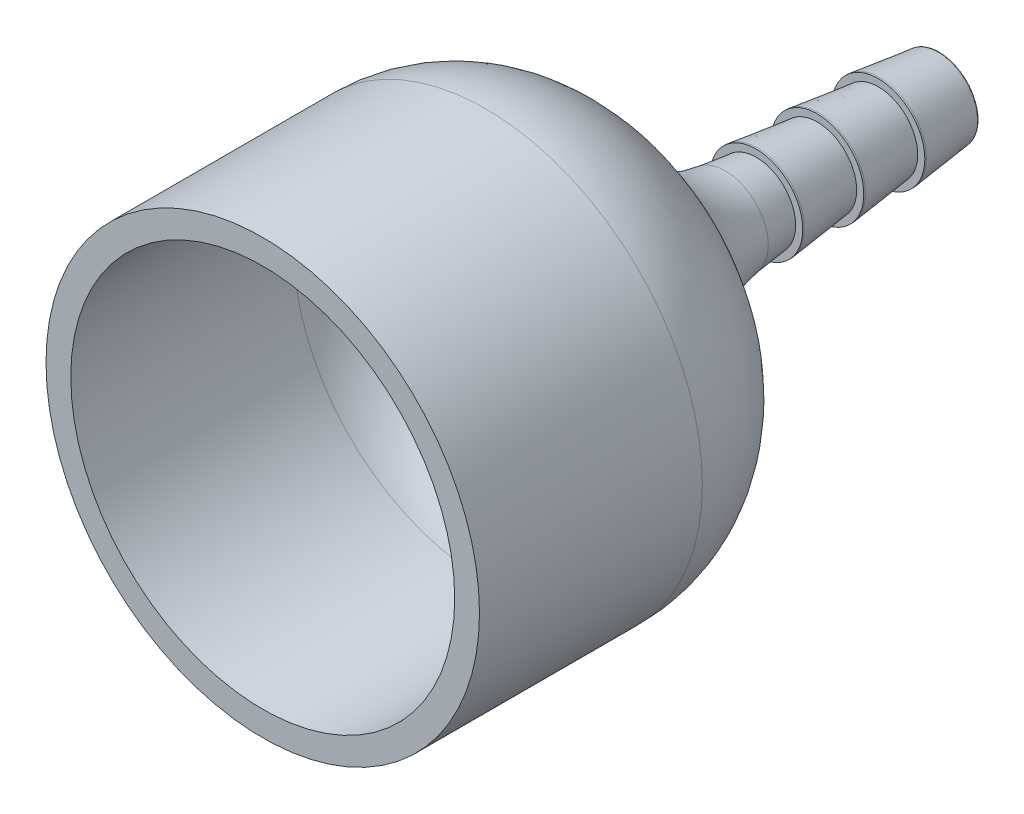
SolidWorks part; units mm, degrees
ref_plane "Front Plane" through (0, 0, 0) normal (0, 0, 1) x (1, 0, 0)
ref_plane "Top Plane" through (0, 0, 0) normal (0, 1, 0) x (1, 0, 0)
ref_plane "Right Plane" through (0, 0, 0) normal (1, 0, 0) x (0, 0, -1)
sketch "Sketch1" plane through (0, 0, 0) normal (0, 1, 0) x (1, 0, 0)
  line L4 (4.3502, 0.893) -> (3.1764, 10.7482)
  line L5 (3.1764, 10.7482) -> (3.7482, 10.7482)
  line L6 (3.7482, 10.7482) -> (3.7482, 10.8752)
  line L7 (3.7482, 10.8752) -> (3.1764, 15.6758)
  line L8 (3.1764, 15.6758) -> (3.7482, 15.6758)
  line L9 (3.7482, 15.6758) -> (3.7482, 15.8028)
  line L10 (3.7482, 15.8028) -> (3.1764, 20.6034)
  line L11 (3.1764, 20.6034) -> (3.7482, 20.6034)
  line L12 (3.7482, 20.6034) -> (3.7482, 20.7304)
  line L13 (3.7482, 20.7304) -> (3.1898, 25.419)
  line L14 (3.0636, 25.531) -> (2.2489, 25.531)
  line L15 (2.2489, 25.531) -> (2.2489, -1.107)
  line L18 (15.5, -11.107) -> (15.5, -29.1028)
  line L19 (17.5, -11.107) -> (17.5, -29.1028)
  line L20 (17.0009, 0.893) -> (17, 0.893)
  line L24 (17.0009, 0.893) -> (17, 0.893)
  line L25 (2.2489, -1.107) -> (5.5, -1.107)
  line L26 (17.5, -29.1028) -> (15.5, -29.1028)
  line L27 (5.5, 0.893) -> (4.3502, 0.893)
  line L34 (0, 25.781) -> (0, -25.781) construction
  arc A0 (5.5, -1.107) -> (15.5, -11.107) centre (5.5, -11.107) cw
  arc A1 (17.5, -11.107) -> (5.5, 0.893) centre (5.5, -11.107) ccw
  spline S0 degree 3 poles (3.1898, 25.419) (3.1864, 25.4476) (3.1714, 25.4785) (3.1229, 25.5208) (3.0911, 25.531) (3.0636, 25.531) knots 0 0 0 0 0.5 0.5 1 1 1 1
  dimension "D7" = 10
  dimension "D1" = 51.562
  dimension "D2" = 15.5
  dimension "D3" = 2
  dimension "D4" = 30
  dimension "D6" = 1.107
revolve "Revolve1" add sketch "Sketch1" angle 360 about L34
fillet "Fillet1" radius 10 1 edges at (4.3502, 0, -0.893)
fillet "Fillet2" radius 1 1 edges at (2.2489, 0, 1.107)
